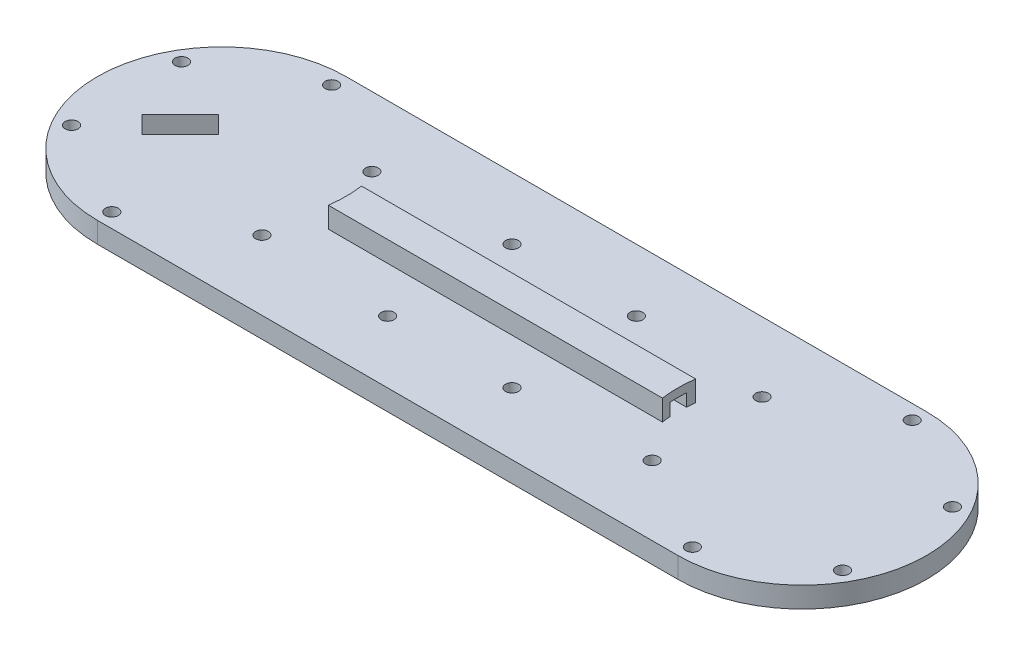
SolidWorks part; units mm, degrees
ref_plane "前视基准面" through (0, 0, 0) normal (0, 0, 1) x (1, 0, 0)
ref_plane "上视基准面" through (0, 0, 0) normal (0, 1, 0) x (1, 0, 0)
ref_plane "右视基准面" through (0, 0, 0) normal (1, 0, 0) x (0, 0, -1)
other "Configuration Table"
sketch "草图1" plane through (0, 0, 0) normal (0, 1, 0) x (1, 0, 0)
  line L14 (-90, 0) -> (-90, 10)
  line L15 (-90, 0) -> (-90, -10)
  line L16 (-70, 30) -> (70, 30)
  line L17 (-70, -30) -> (70, -30)
  line L18 (-90, 10) -> (-70, 10)
  line L19 (90, 0) -> (90, 10)
  line L20 (90, 0) -> (90, -10)
  line L21 (90, 10) -> (70, 10)
  line L22 (70, 10) -> (70, -10)
  line L23 (70, -10) -> (90, -10)
  line L24 (-70, 10) -> (-70, -10)
  line L25 (-70, -10) -> (-90, -10)
  circle A0 centre (-15, 15) radius 1.55
  circle A1 centre (15, 15) radius 1.55
  circle A2 centre (15, -15) radius 1.55
  circle A3 centre (-15, -15) radius 1.55
  arc A4 (70, 30) -> (70, -30) centre (70, 0) cw
  arc A5 (-70, -30) -> (-70, 30) centre (-70, 0) cw
extrude "凸台-拉伸2" add sketch "草图1" along normal blind 5 contours L22 L23 L20 L19 L21 | L25 L24 L18 L14 L15 | A2 | A5 L16 A4 L17 | A1 | A0 | A3
sketch "草图2" plane through (0, 5, 0) normal (0, 1, 0) x (1, 0, 0)
  circle A3 centre (-70, 26.5) radius 1.55
  circle A4 centre (-92.9497, 13.25) radius 1.55
  circle A5 centre (-92.9497, -13.25) radius 1.55
  circle A6 centre (-70, -26.5) radius 1.55
  circle A7 centre (-47.0503, -13.25) radius 1.55
  circle A8 centre (-47.0503, 13.25) radius 1.55
  circle A9 centre (92.9497, 13.25) radius 1.55
  circle A10 centre (92.9497, -13.25) radius 1.55
  circle A11 centre (70, -26.5) radius 1.55
  circle A12 centre (47.0503, -13.25) radius 1.55
  circle A13 centre (47.0503, 13.25) radius 1.55
  circle A14 centre (70, 26.5) radius 1.55
  dimension "D1" = 2
extrude "切除-拉伸2" cut sketch "草图2" against normal blind 5 contours A4 | A6 | A7 | A3 | A12 | A13 | A9 | A10 | A11 | A14 | A5 | A8
sketch "草图3" plane through (0, 5, 0) normal (0, 1, 0) x (1, 0, 0)
  line L1 (-90, 10) -> (-70, 10)
  line L2 (-90, 10) -> (-90, -10)
  line L3 (-90, -10) -> (-70, -10)
  line L4 (-70, 10) -> (-70, -10)
  line L5 (70, 10) -> (90, 10)
  line L6 (70, 10) -> (70, -10)
  line L7 (70, -10) -> (90, -10)
  line L8 (90, 10) -> (90, -10)
extrude "凸台-拉伸4" add sketch "草图3" against normal blind 5
sketch "草图4" plane through (0, 5, 0) normal (0, 1, 0) x (1, 0, 0)
  line L8 (0, 4) -> (40.2679, 4)
  line L9 (0, -4) -> (40.2679, -4)
  line L10 (0, -4) -> (-40.2679, -4)
  line L11 (0, 4) -> (-40.2679, 4)
  arc A2 (40.2679, 4) -> (40.2679, -4) centre (70, 0) ccw
  arc A3 (-40.2679, 4) -> (-40.2679, -4) centre (-70, 0) cw
extrude "凸台-拉伸5" add sketch "草图4" along normal blind 5 contours L10 A3 L11 L8 A2 L9
sketch "草图6" plane through (0, 5, 0) normal (0, 1, 0) x (1, 0, 0)
  line L0 (63.5503, 4) -> (70, 4)
  line L1 (70, 0) -> (70, -4)
  line L2 (70, -4) -> (63.5503, -4)
  line L3 (63.5503, -4) -> (63.5503, 4)
  line L4 (70, 4) -> (70, 0)
extrude "凸台-拉伸6" add sketch "草图6" along normal blind 5 contours L4 L1 L2 L3 L0
sketch "草图7" plane through (70, 0, 0) normal (1, 0, 0) x (0, 0, -1)
  line L1 (4, 5) -> (-4, 5) construction
  line L2 (0, 8) -> (2, 8)
  line L3 (0, 8) -> (-2, 8)
  line L4 (-2, 8) -> (-2, 5)
  line L5 (30, 5) -> (-30, 5) construction
  line L6 (-2, 5) -> (0, 5)
  line L7 (2, 8) -> (2, 5)
  line L8 (2, 5) -> (0, 5)
  line M8 (-4, 5) -> (4, 5)
extrude "切除-拉伸3" cut sketch "草图7" against normal blind 150 contours L7 L2 L3 L4 M8
sketch "草图8" plane through (70, 0, 0) normal (1, 0, 0) x (0, 0, -1)
  line L1 (-4, 5) -> (4, 5)
  line L2 (-4, 5) -> (-4, 10)
  line L3 (-4, 10) -> (4, 10)
  line L4 (4, 5) -> (4, 10)
extrude "切除-拉伸4" cut sketch "草图8" against normal blind 10
sketch "草图9" plane through (0, 0, 0) normal (0, -1, 0) x (1, 0, 0)
  line L9 (-82.1213, -2.1213) -> (-86.7175, 2.4749)
  line L10 (-82.1213, -2.1213) -> (-77.5251, -6.7175)
  line L11 (-77.8787, 2.1213) -> (-82.4749, 6.7175)
  line L12 (-77.8787, 2.1213) -> (-73.2825, -2.4749)
  line L13 (-77.5251, -6.7175) -> (-73.2825, -2.4749)
  line L15 (-82.4749, 6.7175) -> (-86.7175, 2.4749)
extrude "切除-拉伸5" cut sketch "草图9" against normal blind 10 contours L12 L13 L10 L9 L15 L11
equation "\"150】\"=100"
